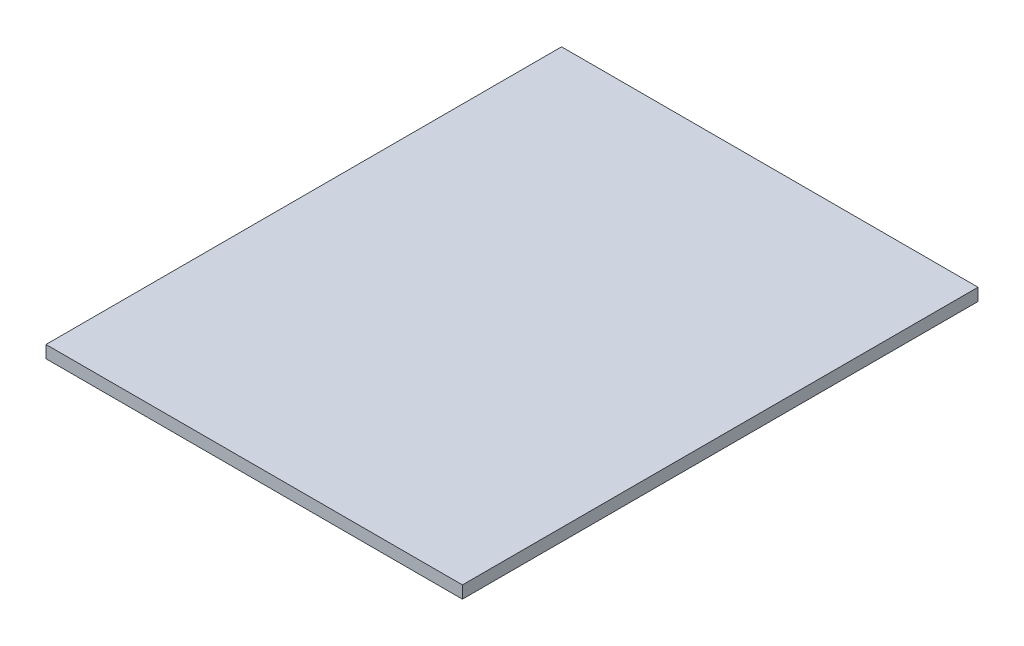
SolidWorks part; units mm, degrees
ref_plane "Front Plane" through (0, 0, 0) normal (0, 0, 1) x (1, 0, 0)
ref_plane "Top Plane" through (0, 0, 0) normal (0, 1, 0) x (1, 0, 0)
ref_plane "Right Plane" through (0, 0, 0) normal (1, 0, 0) x (0, 0, -1)
sketch "Sketch1" plane through (0, 0, 0) normal (0, 1, 0) x (1, 0, 0)
  line L1 (0, 0) -> (21, 0)
  line L2 (0, 0) -> (0, 26)
  line L3 (0, 26) -> (21, 26)
  line L4 (21, 0) -> (21, 26)
  dimension "D1" = 21
  dimension "D2" = 26
extrude "Boss-Extrude1" add sketch "Sketch1" along normal blind 0.625
